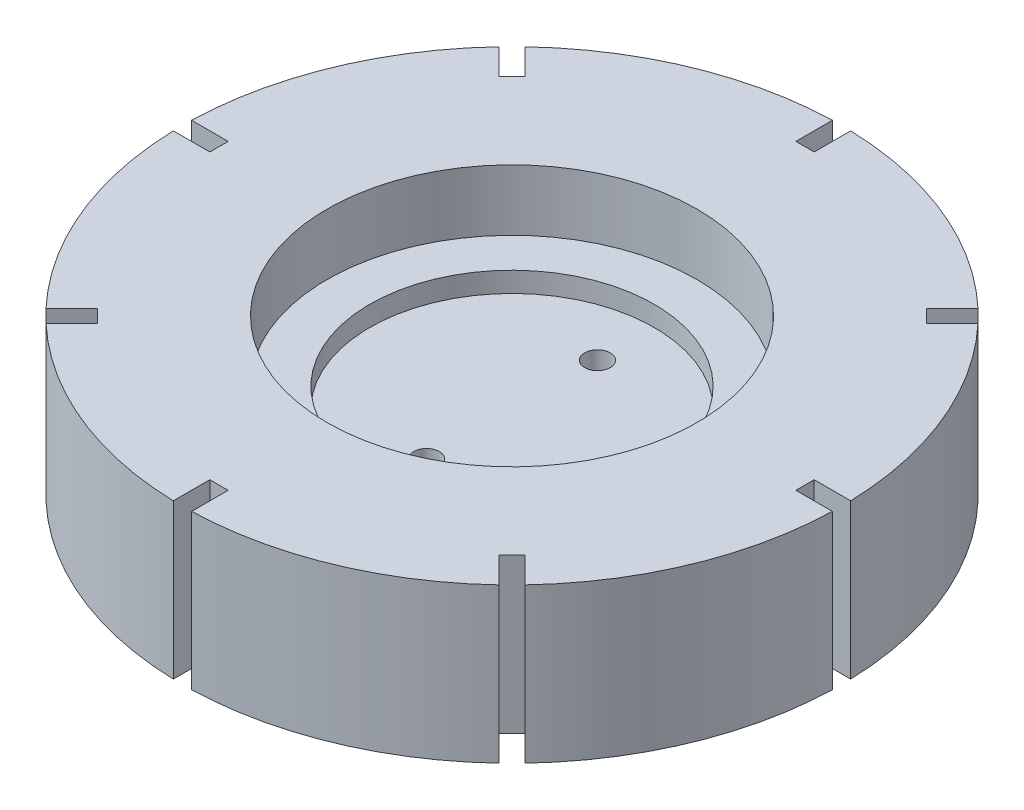
SolidWorks part; units mm, degrees
ref_plane "Front Plane" through (0, 0, 0) normal (0, 0, 1) x (1, 0, 0)
ref_plane "Top Plane" through (0, 0, 0) normal (0, 1, 0) x (1, 0, 0)
ref_plane "Right Plane" through (0, 0, 0) normal (1, 0, 0) x (0, 0, -1)
sketch "Sketch1" plane through (0, 0, 0) normal (0, 1, 0) x (1, 0, 0)
  circle A0 centre (0, 0) radius 11.5 construction
  circle A1 centre (0, 0) radius 7 construction
  circle A2 centre (0, 7) radius 1.05
  circle A3 centre (0, -7) radius 1.05
  circle A6 centre (0, 0) radius 27
  dimension "D1" = 23
  dimension "D2" = 2.1
  dimension "D3" = 14
  dimension "D4" = 54
extrude "Boss-Extrude1" add sketch "Sketch1" along normal blind 3
sketch "Sketch2" plane through (0, 3, 0) normal (0, 1, 0) x (1, 0, 0)
  circle A0 centre (0, 0) radius 11.65
  circle A1 centre (0, 0) radius 27
  dimension "D1" = 23.3
extrude "Boss-Extrude2" add sketch "Sketch2" along normal blind 1.65
sketch "Sketch3" plane through (0, 4.65, 0) normal (0, 1, 0) x (1, 0, 0)
  line L0 (-2.5575, 0) -> (2.5575, 0) construction
  line L1 (-26.971, 1.25) -> (-15.0983, 1.25) construction
  line L5 (-26.971, -1.25) -> (-15.0983, -1.25) construction
  arc A0 (-26.971, -1.25) -> (-26.971, 1.25) centre (0, 0) ccw construction
  circle A2 centre (0, 0) radius 27 construction
  arc A4 (-15.0983, -1.25) -> (-15.0983, 1.25) centre (0, 0) ccw construction
  circle A6 centre (0, 0) radius 15.15
  circle A7 centre (0, 0) radius 27
  dimension "D3" = 15.15
  dimension "D4" = 54
  dimension "D5" = 30.3
  dimension "D1" = 2.5
  dimension "D2" = 1.25
extrude "Boss-Extrude3" add sketch "Sketch3" along normal blind 5
fillet "Fillet1" [suppressed] radius 2.5
sketch "Sketch4" plane through (0, 0, 0) normal (0, -1, 0) x (1, 0, 0)
  circle A0 centre (0, -7) radius 1.875
  circle A1 centre (0, 7) radius 1.875
  circle A2 centre (0, 0) radius 27
  dimension "D1" = 3.75
  dimension "D2" = 3.75
extrude "Boss-Extrude4" add sketch "Sketch4" along normal blind 3
sketch "Sketch5" plane through (0, 9.65, 0) normal (0, 1, 0) x (1, 0, 0)
  line L5 (0, -6.9575) -> (0, 6.9575) construction
  line L6 (-0.75, 27.9703) -> (0.75, 27.9703)
  line L7 (-0.75, 27.9703) -> (-0.75, 24)
  line L8 (-0.75, 24) -> (0.75, 24)
  line L9 (0.75, 27.9703) -> (0.75, 24)
  circle A0 centre (0, 0) radius 27 construction
  point P4 (0, 27.9703)
  dimension "D2" = 3
  dimension "D1" = 1.5
extrude "Cut-Extrude1" cut sketch "Sketch5" against normal through all
pattern_circular "CirPattern1" count 8 over 360 about axis through (0, 0, 0) along (0, 1, 0) of "Cut-Extrude1"
